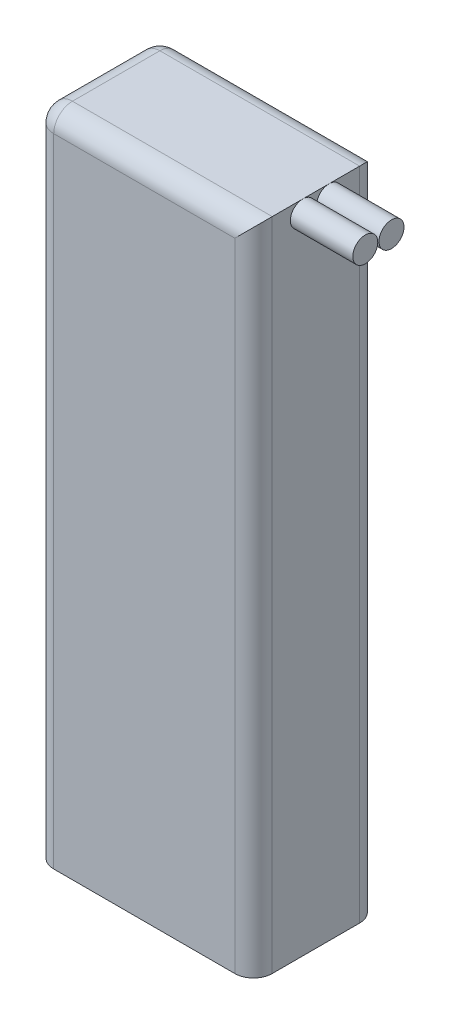
SolidWorks part; units mm, degrees
ref_plane "Front Plane" through (0, 0, 0) normal (0, 0, 1) x (1, 0, 0)
ref_plane "Top Plane" through (0, 0, 0) normal (0, 1, 0) x (1, 0, 0)
ref_plane "Right Plane" through (0, 0, 0) normal (1, 0, 0) x (0, 0, -1)
sketch "Sketch2" plane through (0, 0, 0) normal (0, 1, 0) x (1, 0, 0)
  line L1 (0, 0) -> (35, 0)
  line L2 (0, 0) -> (0, 20)
  line L3 (0, 20) -> (35, 20)
  line L4 (35, 0) -> (35, 20)
  dimension "35" = 35
  dimension "24" = 20
extrude "Boss-Extrude1" add sketch "Sketch2" along normal blind 105
sketch "Sketch5" plane through (35, 0, 0) normal (1, 0, 0) x (0, 0, -1)
  line L0 (20, 105) -> (20, 0) construction
  line L1 (0, 105) -> (0, 0) construction
  line L2 (0, 105) -> (20, 105) construction
  circle A0 centre (7.9, 103) radius 2
  circle A1 centre (12.1, 103) radius 2
  dimension "D1" = 4
  dimension "D2" = 4
  dimension "D3" = 7.9
  dimension "D4" = 7.9
extrude "Boss-Extrude2" add sketch "Sketch5" along normal blind 10
fillet "Fillet1" radius 3 7 edges at (0, 105, -10) (17.5, 105, -20) (0, 52.5, -20) (35, 52.5, -20) (0, 52.5, 0) (35, 52.5, 0) (17.5, 105, 0)
